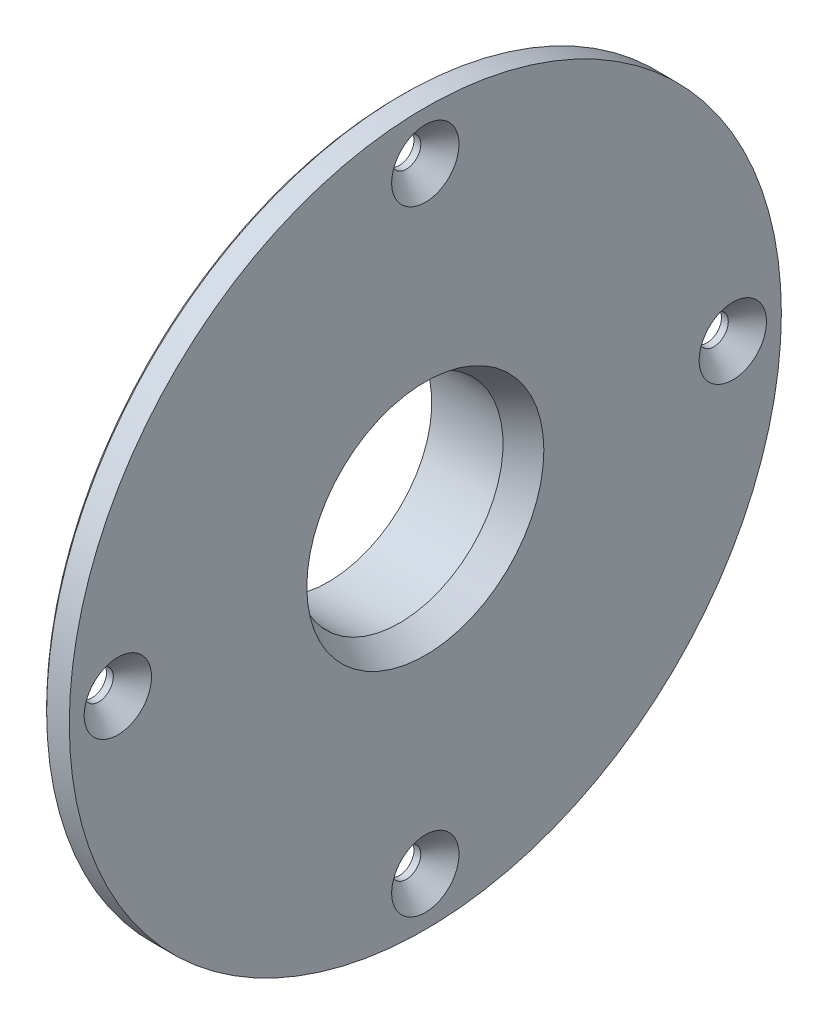
SolidWorks part; units mm, degrees
material "Alliage 6061"
ref_plane "Face" through (0, 0, 0) normal (0, 0, 1) x (1, 0, 0)
ref_plane "Dessus" through (0, 0, 0) normal (0, 1, 0) x (1, 0, 0)
ref_plane "Droite" through (0, 0, 0) normal (1, 0, 0) x (0, 0, -1)
sketch "Esquisse1" plane through (0, 0, 0) normal (0, 0, 1) x (1, 0, 0)
  line L0 (0, 0) -> (54.7909, 0) construction
  line L1 (0, 16) -> (0, 25)
  line L2 (0, 25) -> (7, 25)
  line L3 (11, 26.5) -> (11, 55)
  line L4 (11, 55) -> (15, 55)
  line L5 (11, 26.5) -> (7, 26.5)
  line L6 (7, 26.5) -> (7, 25)
  line L7 (0, 16) -> (15, 16)
  line L8 (15, 55) -> (15, 16)
  dimension "D1" = 32
  dimension "D2" = 50
  dimension "D3" = 7
  dimension "D4" = 53
  dimension "D5" = 4
  dimension "D6" = 110
  dimension "D7" = 4
revolve "Révolution1" add sketch "Esquisse1" angle 360 about L0
sketch "Esquisse2" plane through (15, 0, 0) normal (1, 0, 0) x (0, 0, -1)
  line L0 (47.5, 0) -> (-47.5, 0) construction
  line L1 (0, 47.5) -> (0, -47.5) construction
  circle A0 centre (0, 0) radius 47.5 construction
  circle A1 centre (0, 0) radius 22.5 construction
  dimension "D1" = 95
  dimension "D2" = 45
hole_wizard "Fraisage pour vis à tête fraisée M42" positions "Esquisse6" profile "Esquisse5" countersink size "M4" standard "Din" end condition through all
sketch "Esquisse6" plane through (15, 0, 0) normal (1, 0, 0) x (0, 0, -1)
  point P0 (0, 47.5)
  point P3 (47.5, 0)
  point P6 (0, -47.5)
  point P9 (-47.5, 0)
sketch "Esquisse5" plane through (15, 47.5, 0) normal (0, 1, 0) x (0, 0, -1)
  line L0 (0, 0) -> (0, 15)
  line L1 (0, 15) -> (2.25, 15)
  line L2 (2.25, 15) -> (2.25, 2.95)
  line L3 (2.25, 2.95) -> (5.2, 0)
  line L5 (5.2, 0) -> (0, 0)
  line L6 (-2.25, 2.95) -> (-5.2, 0) construction
  line L11 (0, -6.35) -> (0, 107.95) construction
  dimension "Diamètre du perçage jusqu'au prochain" = 4.5
  dimension "Profondeur du perçage jusqu'au prochain" = 15
  dimension "Diamètre du fraisage entrant" = 10.4
  dimension "Angle du fraisage entrant" = 90
chamfer "Chanfrein1" distance 0.5 angle 45 2 edges at (0, 0, 25) (11, 0, 55)
hole_wizard "Trou taraudé M32" positions "Esquisse10" profile "Esquisse9" tap size "M3" standard "Iso"
sketch "Esquisse10" plane through (0, 0, 0) normal (-1, 0, 0) x (0, 0, 1)
  line L0 (0, 47.5) -> (0, -47.5) construction
  line L1 (-47.5, 0) -> (47.5, 0) construction
  circle A0 centre (0, 0) radius 22.5 construction
  point P0 (0, 22.5)
  point P6 (-22.5, 0)
  point P10 (0, -22.5)
  point P12 (22.5, 0)
sketch "Esquisse9" plane through (0, 22.5, 0) normal (0, 1, 0) x (0, 0, 1)
  line L0 (0, 0) -> (0, 11.2511)
  line L1 (0, 11.2511) -> (1.25, 10.5)
  line L2 (1.25, 10.5) -> (1.25, 0)
  line L5 (1.25, 0) -> (0, 0)
  line L10 (0, 11.2511) -> (-1.25, 10.5) construction
  line L11 (0, -6.35) -> (0, 107.95) construction
  dimension "Diamètre du trou pour taraudage" = 2.5
  dimension "Profondeur du trou pour taraudage" = 10.5
  dimension "Angle de pointe" = 118
cosmetic thread "Filetage de perçage5" parameters "D1"=8, "D2"=3
cosmetic thread "Filetage de perçage6" parameters "D1"=8, "D2"=3
cosmetic thread "Filetage de perçage7" parameters "D1"=8, "D2"=3
cosmetic thread "Filetage de perçage8" parameters "D1"=8, "D2"=3
chamfer "Chanfrein2" distance 4 angle 30 1 edges at (15, 0, 16)
